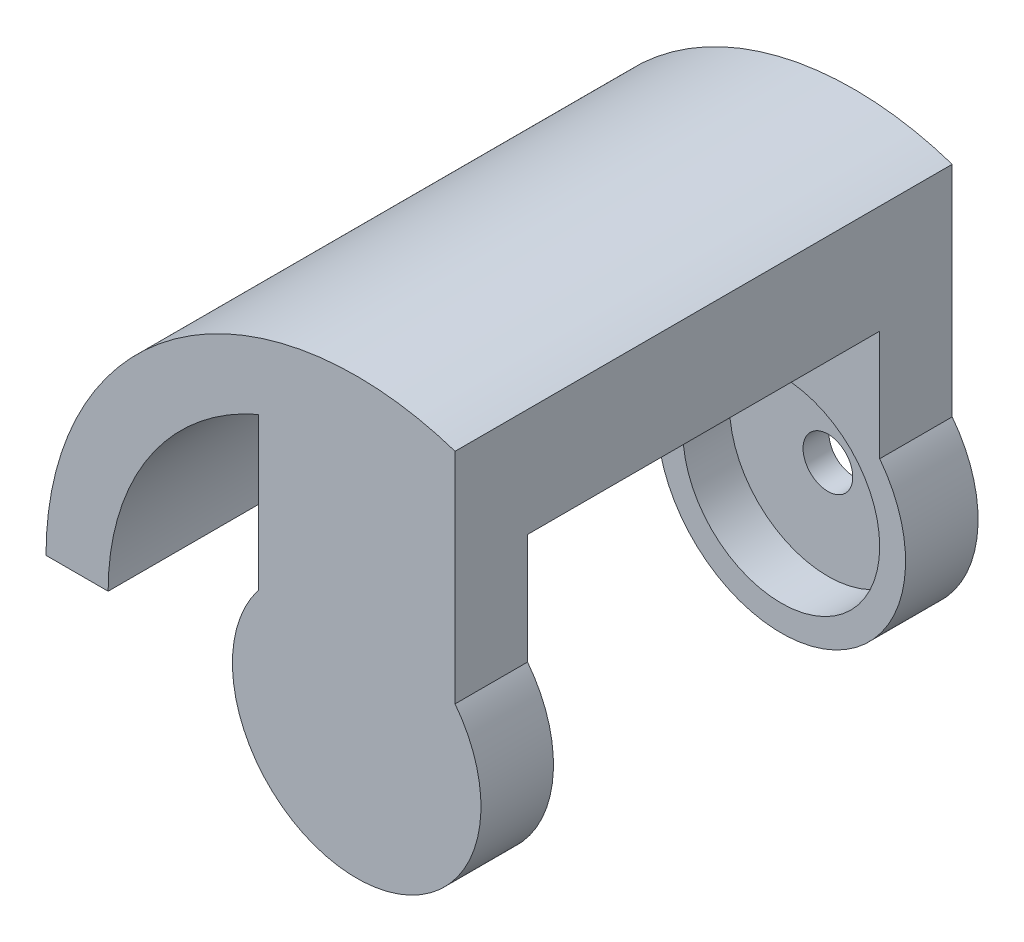
SolidWorks part; units mm, degrees
ref_plane "Front Plane" through (0, 0, 0) normal (0, 0, 1) x (1, 0, 0)
ref_plane "Top Plane" through (0, 0, 0) normal (0, 1, 0) x (1, 0, 0)
ref_plane "Right Plane" through (0, 0, 0) normal (1, 0, 0) x (0, 0, -1)
sketch "Sketch1" plane through (0, 0, 0) normal (0, 0, 1) x (1, 0, 0)
  line L0 (0, 0) -> (0, 30) construction
  line L1 (-12, 0) -> (-12, 30)
  line L2 (12, 0) -> (12, 30)
  line L3 (-12, 30) -> (12, 30)
  line L5 (-12, 30) -> (12, 30)
  line L6 (-12, 30) -> (-12, 26)
  line L7 (-12, 26) -> (12, 26)
  line L8 (12, 30) -> (12, 26)
  circle A0 centre (0, 0) radius 9.5
  arc A2 (-12, 0) -> (12, 0) centre (0, 0) ccw
  arc A3 (12, 30) -> (-12, 30) centre (0, 30) ccw
  point P3 (0, 15)
  dimension "D1" = 19
  dimension "D2" = 30
  dimension "D3" = 12
  dimension "D4" = 4
extrude "Boss-Extrude1" add sketch "Sketch1" against normal blind 48
sketch "Sketch2" plane through (-12, 0, 0) normal (-1, 0, 0) x (0, 0, 1)
  line L0 (-48, -12) -> (0, -12) construction
  line L1 (-7, -12) -> (-41, -12)
  line L2 (-7, -12) -> (-7, 18)
  line L3 (-7, 18) -> (-41, 18)
  line L4 (-41, -12) -> (-41, 18)
  line L5 (-48, 0) -> (-48, 30) construction
  line L6 (0, -12) -> (0, 0) construction
  dimension "D1" = 7
  dimension "D2" = 7
  dimension "D3" = 30
extrude "Cut-Extrude1" cut sketch "Sketch2" against normal through all
sketch "Sketch3" plane through (0, 0, -48) normal (0, 0, -1) x (-1, 0, 0)
  circle A0 centre (0, 0) radius 9.5
  circle A1 centre (0, 0) radius 2.4
  dimension "D1" = 4.8
  dimension "D2" = 19
extrude "Boss-Extrude2" add sketch "Sketch3" against normal blind 2.5
sketch "Sketch4" plane through (0, 0, 0) normal (0, 0, 1) x (1, 0, 0)
  circle A0 centre (0, 0) radius 9.5
  circle A1 centre (0, 0) radius 4.2
  dimension "D1" = 19
  dimension "D2" = 8.4
extrude "Boss-Extrude3" add sketch "Sketch4" against normal blind 7
sketch "Sketch5" plane through (0, 0, 0) normal (0, 0, 1) x (1, 0, 0)
  circle A0 centre (0, 0) radius 4.2
extrude "Boss-Extrude4" add sketch "Sketch5" against normal blind 11
sketch "Sketch6" plane through (0, 0, -48) normal (0, 0, -1) x (-1, 0, 0)
  line L0 (0, 0) -> (30, 0)
  line L1 (-12, 30) -> (12, 30)
  line L2 (-12, 30) -> (-12, 0)
  line L3 (-12, 0) -> (12, 0)
  line L4 (12, 30) -> (12, 0)
  line L5 (-9.5, 0) -> (9.5, 0)
  line L6 (-9.5, 0) -> (-9.5, 30)
  line L7 (-9.5, 30) -> (9.5, 30)
  line L8 (9.5, 0) -> (9.5, 30)
  line L9 (30, 0) -> (0, 0)
  line L10 (0, 0) -> (21.2132, 21.2132)
  circle A0 centre (0, 0) radius 12
  circle A1 centre (0, 0) radius 30
  circle A2 centre (0, 0) radius 24
  circle A3 centre (0, 0) radius 9.5 construction
  line M1 (-12, 30) -> (-12, 0)
  line M3 (12, 0) -> (12, 30)
  line M4 (12, 30) -> (-12, 30)
  dimension "D1" = 48
  dimension "D2" = 60
  dimension "D3" = 45
extrude "Cut-Extrude2" cut sketch "Sketch6" against normal through all contours A1 L6 L1 M1 | A1 L7 L6 | A1 L8 L1 | A1 L8 M3 M4 | L6 A2 A0 M1 | A2 L6 A1 L2 | L4 A2 L8 L10 | A0 L10 L8 M3
sketch "Sketch7" plane through (0, 0, -48) normal (0, 0, -1) x (-1, 0, 0)
  line L0 (0, 0) -> (30, 0)
  line L1 (30, 0) -> (0, 0)
  line L2 (0, 0) -> (21.2132, 21.2132)
  circle A0 centre (0, 0) radius 30
  circle A1 centre (0, 0) radius 24
  line M7 (12, 20.7846) -> (12, 27.4955)
  dimension "D1" = 60
  dimension "D2" = 48
  dimension "D3" = 45
extrude "Boss-Extrude5" add sketch "Sketch7" against normal blind 48 contours A1 L2 A0 M7 | A1 L1 A0 L2
